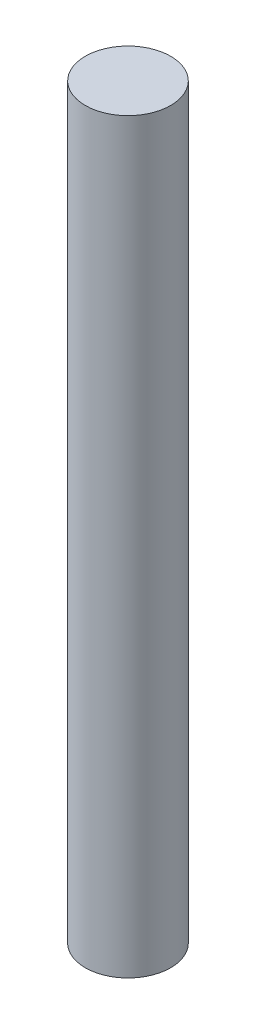
SolidWorks part; units mm, degrees
ref_plane "Front Plane" through (0, 0, 0) normal (0, 0, 1) x (1, 0, 0)
ref_plane "Top Plane" through (0, 0, 0) normal (0, 1, 0) x (1, 0, 0)
ref_plane "Right Plane" through (0, 0, 0) normal (1, 0, 0) x (0, 0, -1)
sketch "Sketch1" plane through (0, 0, 0) normal (0, 1, 0) x (1, 0, 0)
  circle A0 centre (0, 0) radius 4000
  dimension "D1" = 8000
extrude "Boss-Extrude1" add sketch "Sketch1" along normal blind 70000
